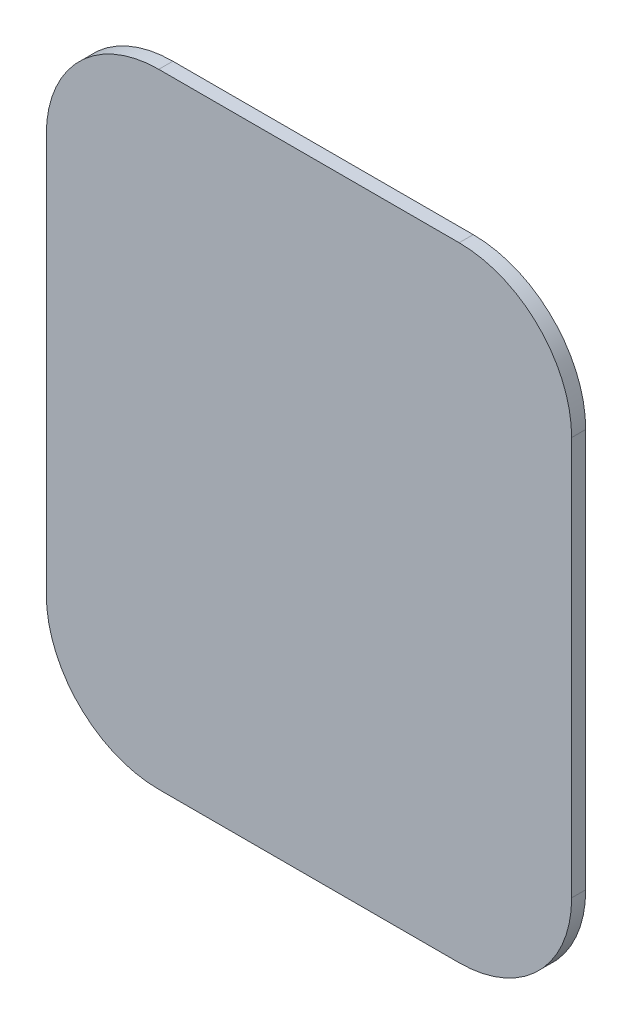
SolidWorks part; units mm, degrees
ref_plane "前视基准面" through (0, 0, 0) normal (0, 0, 1) x (1, 0, 0)
ref_plane "上视基准面" through (0, 0, 0) normal (0, 1, 0) x (1, 0, 0)
ref_plane "右视基准面" through (0, 0, 0) normal (1, 0, 0) x (0, 0, -1)
other "Configuration Table"
sketch "草图2" plane through (0, 0, 0) normal (0, 0, 1) x (1, 0, 0)
  line L1 (-10.6827, 22.1764) -> (10.6827, 22.1764)
  line L2 (-18.6827, 14.1764) -> (-18.6827, -14.1764)
  line L3 (-10.6827, -22.1764) -> (10.6827, -22.1764)
  line L4 (18.6827, 14.1764) -> (18.6827, -14.1764)
  line L5 (0, -22.1764) -> (0, 22.1764) construction
  line L6 (-18.6827, 0) -> (18.6827, 0) construction
  arc A0 (-18.6827, -14.1764) -> (-10.6827, -22.1764) centre (-10.6827, -14.1764) ccw
  arc A1 (10.6827, -22.1764) -> (18.6827, -14.1764) centre (10.6827, -14.1764) ccw
  arc A2 (10.6827, 22.1764) -> (18.6827, 14.1764) centre (10.6827, 14.1764) cw
  arc A3 (-10.6827, 22.1764) -> (-18.6827, 14.1764) centre (-10.6827, 14.1764) ccw
  point P0 (0, 0)
  point P6 (-18.6827, -22.1764)
  point P11 (18.6827, 22.1764)
  point P15 (-18.6827, 22.1764)
  dimension "D3" = 8
  dimension "D1" = 37.3654
  dimension "D2" = 44.3527
extrude "凸台-拉伸1" add sketch "草图2" along normal blind 1 contours L1 A3 L2 A0 L3 A1 L4 A2
